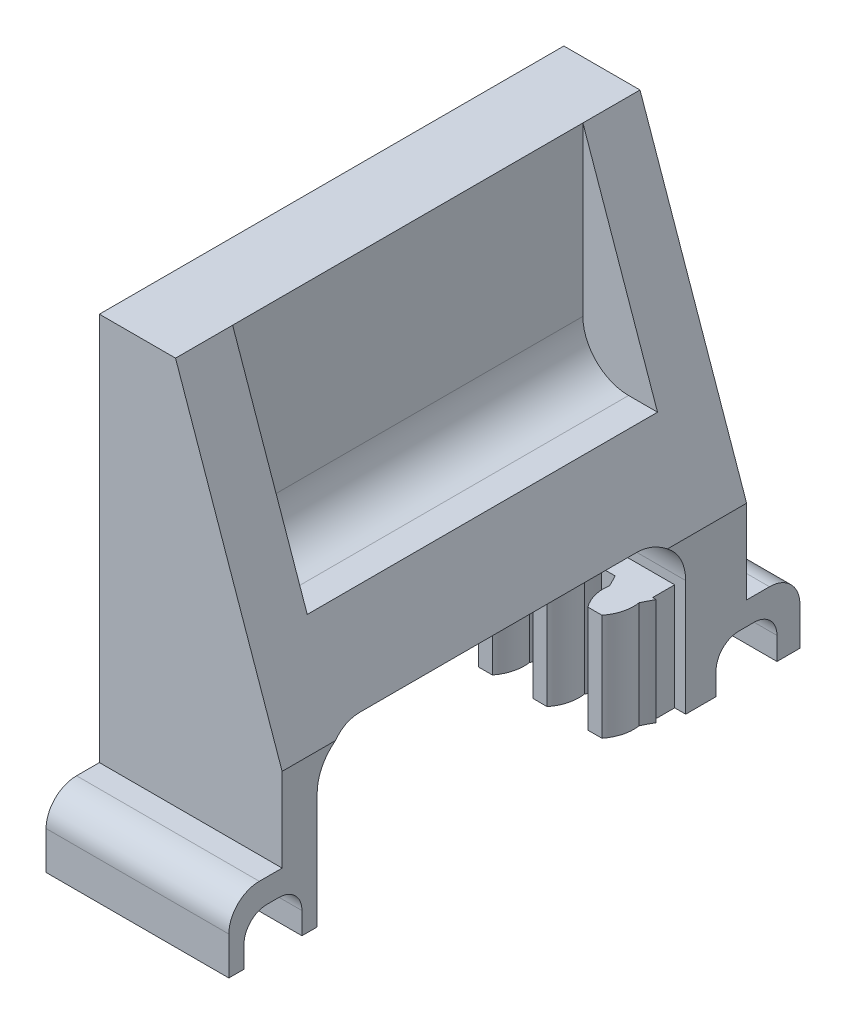
SolidWorks part; units mm, degrees
ref_plane "Front Plane" through (0, 0, 0) normal (0, 0, 1) x (1, 0, 0)
ref_plane "Top Plane" through (0, 0, 0) normal (0, 1, 0) x (1, 0, 0)
ref_plane "Right Plane" through (0, 0, 0) normal (1, 0, 0) x (0, 0, -1)
sketch "Sketch1" plane through (0, 0, 0) normal (0, 0, 1) x (1, 0, 0)
  line L0 (0, 0) -> (0, -30)
  line L1 (0, -30) -> (12, -30)
  line L2 (12, -30) -> (12, -20)
  line L3 (12, -20) -> (5, 0)
  line L4 (5, 0) -> (0, 0)
  dimension "D1" = 30
  dimension "D2" = 12
  dimension "D3" = 10
  dimension "D4" = 5
extrude "Boss-Extrude1" add sketch "Sketch1" against normal blind 30.5
sketch "Sketch4" plane through (0, 0, 0) normal (-1, 0, 0) x (0, 0, 1)
  line L0 (-30.5, 0) -> (-30.5, -30) construction
  line L1 (-26.5, -19.3999) -> (-2.3, -19.3999)
  line L2 (-26.5, -19.3999) -> (-26.5, -32.3999)
  line L3 (-26.5, -32.3999) -> (-2.3, -32.3999)
  line L4 (-2.3, -19.3999) -> (-2.3, -32.3999)
  point P4 (-26.5, -25.8999)
  dimension "D1" = 24.2
  dimension "D2" = 13
  dimension "D3" = 4
extrude "Cut-Extrude2" cut sketch "Sketch4" against normal blind 25 contours L2 L1 L4 L3
ref_plane "Plane1" through (0, 0, -15.25) normal (0, 0, 1) x (1, 0, 0)
sketch "Sketch6" plane through (0, 0, -15.25) normal (0, 0, 1) x (1, 0, 0)
  line L0 (5, 0) -> (5, -14)
  line L1 (5, -14) -> (9.9, -14)
  line L2 (12, -20) -> (5, 0) construction
  line L3 (9.9, -14) -> (5, 0)
  dimension "D1" = 14
extrude "Cut-Extrude4" cut sketch "Sketch6" against normal mid plane 23
ref_plane "Plane2" through (0, -26.4, 0) normal (0, 1, 0) x (1, 0, 0)
ref_plane "Plane3" through (0, -30, 0) normal (0, 1, 0) x (1, 0, 0)
sketch "Sketch7" plane through (0, -30, 0) normal (0, 1, 0) x (1, 0, 0)
  line L0 (11.2768, 26.75) -> (-19.7232, 26.75)
  line L62 (-6.6, 15.25) -> (6.6, 15.25) construction
  line L162 (11.2768, 26.75) -> (11.2768, 25.05)
  line L172 (-19.7232, 25.05) -> (-19.7232, 26.75)
  line L243 (11.2768, 25.05) -> (-19.7232, 25.05)
  dimension "D2" = 31
  dimension "D3" = 1.7
  dimension "D7" = 11.5
extrude "Boss-Extrude3" add sketch "Sketch7" along normal blind 7
sketch "Sketch10" plane through (0, -30, 0) normal (0, 1, 0) x (1, 0, 0)
  line L1 (10.1614, 22.3812) -> (10.1614, 23.4692) construction
  line L2 (10.6216, 22.3812) -> (9.7011, 22.3812)
  line L4 (-19.7232, 25.05) -> (11.2768, 25.05) construction
  line L5 (8.8114, 25.05) -> (11.5114, 25.05)
  arc A0 (10.6216, 22.3812) -> (11.1326, 24.3117) centre (8.6412, 23.9382) ccw
  arc A1 (11.1326, 24.3117) -> (11.5114, 25.05) centre (19.4957, 20.4874) cw
  arc A2 (9.1902, 24.3117) -> (8.8114, 25.05) centre (0.827, 20.4874) ccw
  arc A3 (9.7011, 22.3812) -> (9.1902, 24.3117) centre (11.6815, 23.9382) cw
  dimension "D1" = 2.7
extrude "Boss-Extrude4" add sketch "Sketch10" along normal blind 7
pattern_linear "LPattern1" count 8 spacing 3.6 along (-1, 0, 0) of "Boss-Extrude4"
sketch "Sketch11" plane through (0, 0, -30.5) normal (0, 0, -1) x (-1, 0, 0)
  line L0 (-12, -30) -> (-12, -20) construction
  line L1 (-12, -25.5) -> (0, -25.5)
  line L2 (-12, -25.5) -> (-12, -30)
  line L3 (-12, -30) -> (0, -30)
  line L4 (0, -25.5) -> (0, -30)
  dimension "D1" = 4.5
extrude "Boss-Extrude5" add sketch "Sketch11" along normal blind 3.5
fillet "Fillet1" radius 2 1 edges at (6, -25.5, -34)
mirror "Mirror1" about plane through (0, 0, -15.25) normal (0, 0, 1) of "Boss-Extrude5"
fillet "Fillet2" radius 2 1 edges at (6, -25.5, 3.5)
fillet "Fillet5" radius 3 3 edges at (5, -14, -15.25) (5.895, -19.3999, -2.3) (5.895, -19.3999, -26.5)
sketch "Sketch12" plane through (0, 0, 0) normal (-1, 0, 0) x (0, 0, 1)
  line L0 (-15.25, -20.6354) -> (-15.25, -36.9741) construction
  line L1 (-32.4946, -27.0184) -> (-28.4946, -27.0184)
  line L2 (-32.4946, -27.0184) -> (-32.4946, -30.5184)
  line L3 (-32.4946, -30.5184) -> (-28.4946, -30.5184)
  line L4 (-28.4946, -27.0184) -> (-28.4946, -30.5184)
  line L5 (-2.3, -30) -> (-2.3, -22.3999) construction
  line L11 (-15.25, -16.5) -> (-15.25, 16.5) construction
  line L12 (2.5, -30.5644) -> (-1.3, -30.5644)
  line L13 (-1.3, -27.0644) -> (-1.3, -30.5644)
  line L14 (2.5, -27.0644) -> (-1.3, -27.0644)
  line L15 (2.5, -27.0644) -> (2.5, -30.5644)
  dimension "D1" = 4
  dimension "D2" = 3.5
  dimension "D3" = 1
extrude "Cut-Extrude5" cut sketch "Sketch12" against normal up to surface (12 mm away) up to face at (12, -25.043, -29.9997)
fillet "Fillet6" radius 1.5 4 edges at (6, -27.0184, -32.4946) (6, -27.0184, -28.4946) (6, -27.0644, 2.5) (6, -27.0644, -1.3)
